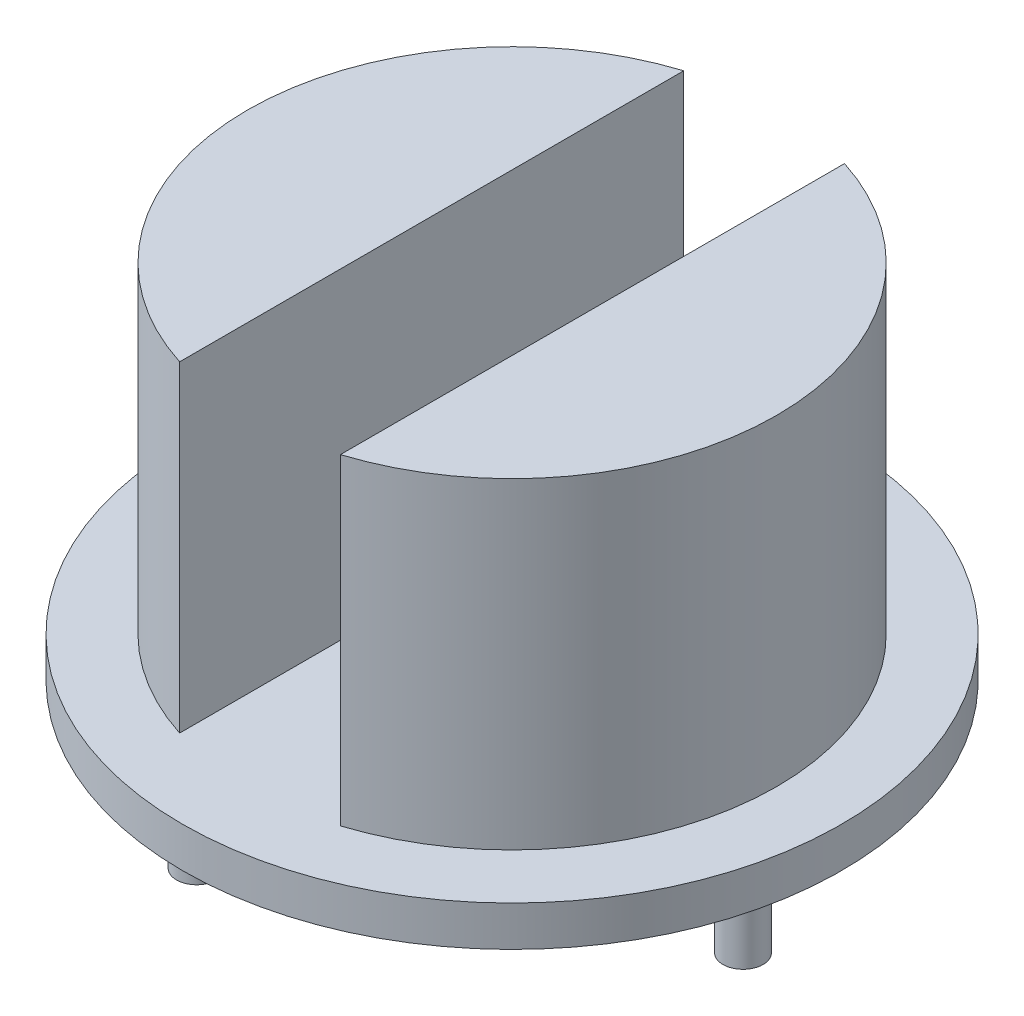
SolidWorks part; units mm, degrees
ref_plane "Front Plane" through (0, 0, 0) normal (0, 0, 1) x (1, 0, 0)
ref_plane "Top Plane" through (0, 0, 0) normal (0, 1, 0) x (1, 0, 0)
ref_plane "Right Plane" through (0, 0, 0) normal (1, 0, 0) x (0, 0, -1)
sketch "Sketch1" plane through (0, 0, 0) normal (0, 1, 0) x (1, 0, 0)
  circle A0 centre (0, 0) radius 41
  dimension "D1" = 82
extrude "Boss-Extrude1" add sketch "Sketch1" along normal blind 5
sketch "Sketch2" plane through (0, 0, 0) normal (0, -1, 0) x (1, 0, 0)
  circle A0 centre (0, 0) radius 28.7301 construction
  circle A2 centre (28.7301, 0) radius 2.5
  circle A3 centre (-14.365, 24.881) radius 2.5
  circle A4 centre (-14.365, -24.881) radius 2.5
extrude "Boss-Extrude2" add sketch "Sketch2" along normal blind 15
sketch "Sketch3" plane through (0, 5, 0) normal (0, 1, 0) x (1, 0, 0)
  line L2 (-10, 31.3562) -> (-10, -31.3562)
  line L4 (10, 31.3562) -> (10, -31.3562)
  line L5 (-10, 31.3562) -> (10, -31.3562) construction
  line L6 (-10, -31.3562) -> (10, 31.3562) construction
  circle A0 centre (0, 0) radius 28.73 construction
  arc A1 (-10, 31.3562) -> (-10, -31.3562) centre (0, 0) ccw
  arc A2 (10, -31.3562) -> (10, 31.3562) centre (0, 0) ccw
  dimension "D1" = 20
extrude "Boss-Extrude3" add sketch "Sketch3" along normal blind 40
